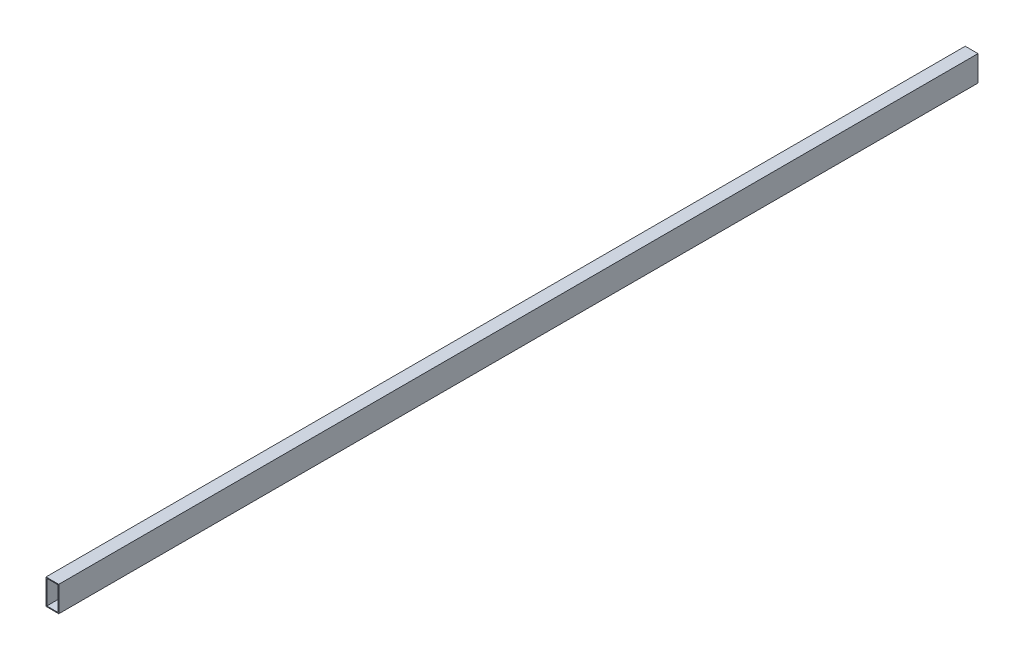
SolidWorks part; units mm, degrees
ref_plane "Front Plane" through (0, 0, 0) normal (0, 0, 1) x (1, 0, 0)
ref_plane "Top Plane" through (0, 0, 0) normal (0, 1, 0) x (1, 0, 0)
ref_plane "Right Plane" through (0, 0, 0) normal (1, 0, 0) x (0, 0, -1)
sketch "Sketch1" plane through (0, 0, 0) normal (0, 0, 1) x (1, 0, 0)
  line L0 (0, 23.8252) -> (0, 25.4) construction
  line L1 (-12.7, -25.4) -> (12.7, -25.4)
  line L2 (-12.7, -25.4) -> (-12.7, 25.4)
  line L3 (-12.7, 25.4) -> (12.7, 25.4)
  line L4 (12.7, -25.4) -> (12.7, 25.4)
  line L5 (-12.7, -25.4) -> (12.7, 25.4) construction
  line L6 (-12.7, 25.4) -> (12.7, -25.4) construction
  line L7 (-11.1252, -23.8252) -> (11.1252, -23.8252)
  line L8 (-11.1252, -23.8252) -> (-11.1252, 23.8252)
  line L9 (-11.1252, 23.8252) -> (11.1252, 23.8252)
  line L10 (11.1252, -23.8252) -> (11.1252, 23.8252)
  line L11 (-11.1252, -23.8252) -> (11.1252, 23.8252) construction
  line L12 (-11.1252, 23.8252) -> (11.1252, -23.8252) construction
  line L13 (-11.1252, 0) -> (-12.7, 0) construction
  point P0 (0, 0)
  point P6 (0, 0)
  dimension "D1" = 50.8
  dimension "D2" = 25.4
  dimension "D3" = 1.5748
extrude "Boss-Extrude1" add sketch "Sketch1" along normal blind 1828.8
